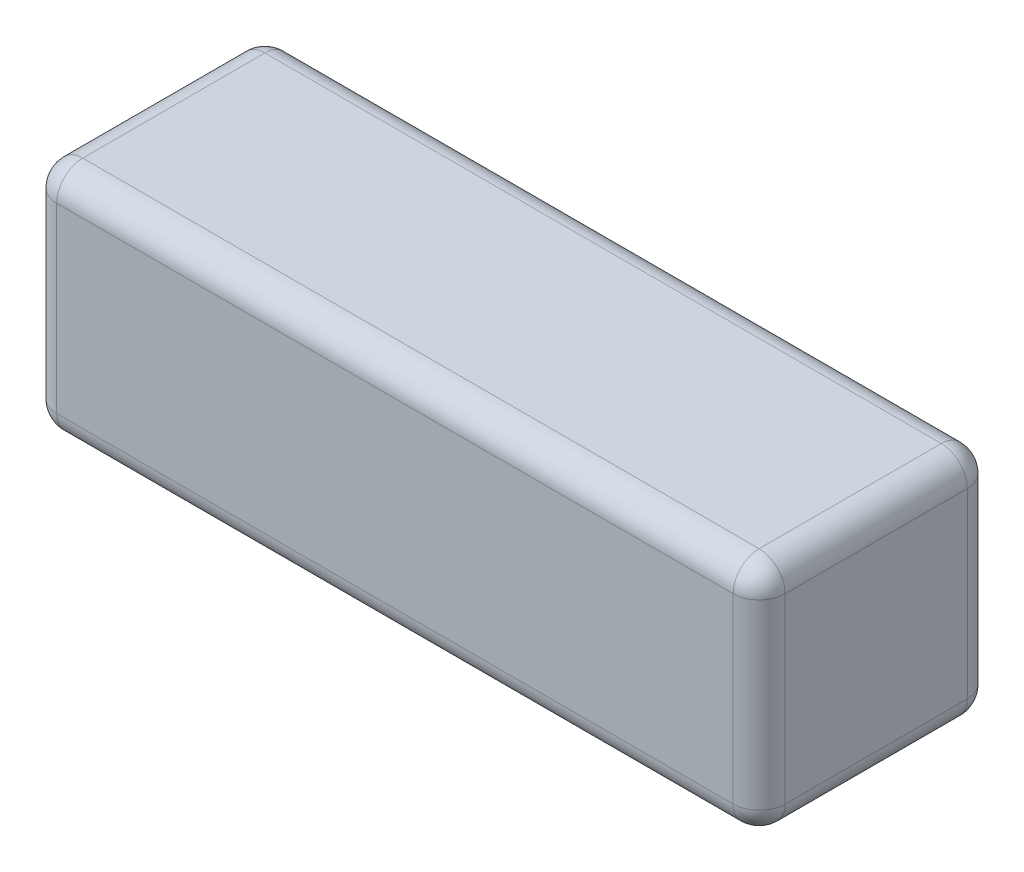
SolidWorks part; units mm, degrees
ref_plane "Front Plane" through (0, 0, 0) normal (0, 0, 1) x (1, 0, 0)
ref_plane "Top Plane" through (0, 0, 0) normal (0, 1, 0) x (1, 0, 0)
ref_plane "Right Plane" through (0, 0, 0) normal (1, 0, 0) x (0, 0, -1)
sketch "Sketch2" plane through (0, 0, 0) normal (0, 0, 1) x (1, 0, 0)
  line L1 (-70, -22.5) -> (70, -22.5)
  line L2 (-70, -22.5) -> (-70, 22.5)
  line L3 (-70, 22.5) -> (70, 22.5)
  line L4 (70, -22.5) -> (70, 22.5)
  line L5 (-70, -22.5) -> (70, 22.5) construction
  line L6 (-70, 22.5) -> (70, -22.5) construction
  point P0 (0, 0)
  dimension "D1" = 140
  dimension "D2" = 45
extrude "Boss-Extrude1" add sketch "Sketch2" along normal blind 45
fillet "Fillet1" radius 5 12 edges at (-70, 0, 0) (70, 0, 0) (-70, 0, 45) (70, 0, 45) (-70, -22.5, 22.5) (0, -22.5, 45) (70, -22.5, 22.5) (0, -22.5, 0) (70, 22.5, 22.5) (0, 22.5, 45) (-70, 22.5, 22.5) (0, 22.5, 0)
